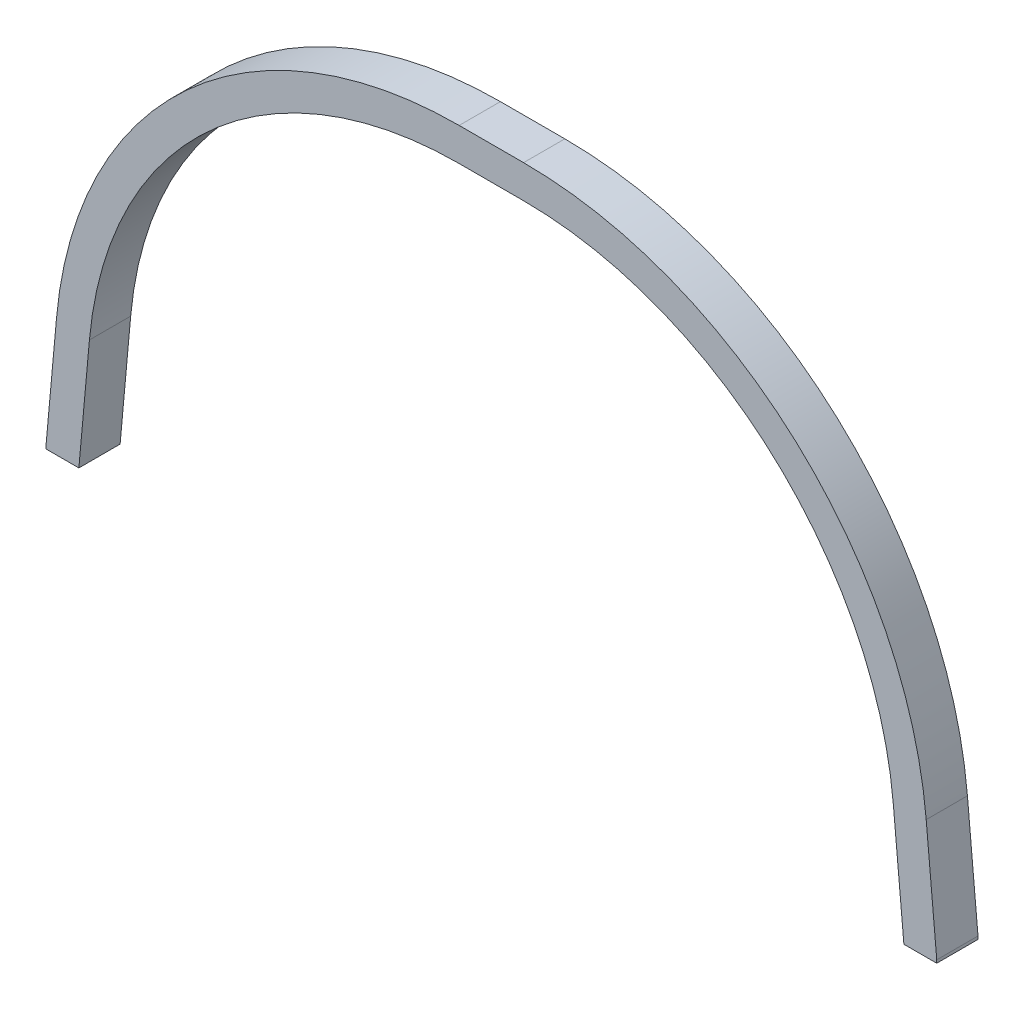
SolidWorks part; units mm, degrees
ref_plane "Front" through (0, 0, 0) normal (0, 0, 1) x (1, 0, 0)
ref_plane "Top" through (0, 0, 0) normal (0, 1, 0) x (1, 0, 0)
ref_plane "Right" through (0, 0, 0) normal (1, 0, 0) x (0, 0, -1)
sketch "草图1" plane through (0, 0, 0) normal (0, 0, 1) x (1, 0, 0)
  line L0 (0, 0) -> (0, 85)
  line L3 (125, 175) -> (355, 175)
  line L4 (355, 175) -> (355, 0)
  line L5 (355, 0) -> (317.5, 0)
  line L7 (312.5, 60) -> (222.5, 60)
  line L9 (217.5, 0) -> (137.5, 0)
  line L11 (132.5, 60) -> (42.5, 60)
  line L13 (37.5, 0) -> (0, 0)
  line L14 (37.5, 0) -> (37.5, 5)
  line L15 (37.5, 5) -> (42.5, 60)
  line L16 (137.5, 0) -> (137.5, 5)
  line L17 (137.5, 5) -> (132.5, 60)
  line L18 (217.5, 0) -> (217.5, 5)
  line L19 (217.5, 5) -> (222.5, 60)
  line L22 (312.5, 60) -> (317.5, 5)
  line L23 (317.5, 5) -> (317.5, 0)
  line L24 (125, 175) -> (110, 105)
  line L25 (110, 105) -> (0, 85)
  dimension "D1" = 85
  dimension "D2" = 37.5
  dimension "D3" = 0
  dimension "D4" = 100
  dimension "D5" = 90
  dimension "D6" = 80
  dimension "D7" = 100
  dimension "D8" = 90
  dimension "D9" = 37.5
  dimension "D10" = 70
  dimension "D11" = 20
  dimension "D12" = 5
  dimension "D13" = 15
  dimension "D15" = 60
  dimension "D16" = 60
  dimension "D18" = 230
  dimension "D19" = 5
  dimension "D20" = 5
  dimension "D21" = 5
extrude "凸台-拉伸1" add sketch "草图1" along normal blind 5
sketch "草图2" plane through (0, 0, 5) normal (0, 0, 1) x (1, 0, 0)
  line L0 (355, 175) -> (125, 175) construction
  circle A1 centre (200, 173) radius 1
  circle A2 centre (240, 173) radius 1
  circle A3 centre (280, 173) radius 1
  circle A4 centre (320, 173) radius 1
  circle A5 centre (160, 173) radius 1
  dimension "D2" = 2
  dimension "D3" = 40
  dimension "D4" = 2
  dimension "D7" = 0
  dimension "D8" = 40
  dimension "D9" = 40
  dimension "D10" = 2
  dimension "D11" = 40
  dimension "D12" = 0
sketch "草图3" plane through (0, 0, 5) normal (0, 0, 1) x (1, 0, 0)
  line L0 (355, 175) -> (125, 175) construction
  line L4 (167.5, 175) -> (167.5, 172)
  line L5 (355, 172) -> (327.5, 172)
  line L9 (207.5, 175) -> (207.5, 172)
  line L13 (247.5, 175) -> (247.5, 172)
  line L17 (287.5, 175) -> (287.5, 172)
  line L19 (312.5, 175) -> (312.5, 172)
  line L21 (327.5, 175) -> (327.5, 172)
  line L22 (355, 0) -> (355, 175) construction
  line L25 (192.5, 172) -> (167.5, 172)
  line L26 (232.5, 172) -> (207.5, 172)
  line L27 (272.5, 172) -> (247.5, 172)
  line L28 (312.5, 172) -> (287.5, 172)
  line L31 (167.5, 175) -> (192.5, 175)
  line L32 (207.5, 175) -> (232.5, 175)
  line L33 (247.5, 175) -> (272.5, 175)
  line L34 (287.5, 175) -> (312.5, 175)
  line L35 (327.5, 175) -> (355, 175)
  line L36 (355, 175) -> (355, 172)
  line L37 (152.5, 175) -> (152.5, 172)
  line L38 (192.5, 175) -> (192.5, 172)
  line L39 (232.5, 175) -> (232.5, 172)
  line L40 (272.5, 175) -> (272.5, 172)
  line L41 (152.5, 172) -> (124.3571, 172)
  line L42 (125, 175) -> (110, 105) construction
  line L44 (152.5, 175) -> (125, 175)
  line L45 (125, 175) -> (124.3571, 172)
  circle A4 centre (320, 173) radius 1 construction
  dimension "D15" = 7.5
  dimension "D1" = 15
  dimension "D2" = 3
  dimension "D4" = 3
  dimension "D5" = 15
  dimension "D7" = 3
  dimension "D8" = 15
  dimension "D10" = 3
  dimension "D11" = 15
  dimension "D13" = 15
  dimension "D14" = 3
extrude "切除-拉伸1" cut sketch "草图3" against normal through all
extrude "切除-拉伸2" cut sketch "草图2" against normal through all
sketch "草图4" plane through (0, 0, 5) normal (0, 0, 1) x (1, 0, 0)
  line L0 (355, 0) -> (355, 172) construction
  line L1 (327.5, 172) -> (355, 172) construction
  circle A0 centre (353, 162) radius 1
  circle A1 centre (353, 122) radius 1
  circle A2 centre (353, 82) radius 1
  circle A3 centre (353, 42) radius 1
  dimension "D1" = 2
  dimension "D2" = 2
  dimension "D3" = 2
  dimension "D4" = 40
  dimension "D5" = 40
  dimension "D6" = 2
  dimension "D7" = 40
  dimension "D8" = 10
extrude "切除-拉伸3" cut sketch "草图4" against normal through all
sketch "草图5" plane through (0, 0, 5) normal (0, 0, 1) x (1, 0, 0)
  line L0 (355, 0) -> (355, 172) construction
  line L1 (355, 152) -> (352, 152)
  line L2 (355, 152) -> (355, 132)
  line L3 (355, 132) -> (352, 132)
  line L4 (352, 152) -> (352, 132)
  line L6 (355, 112) -> (352, 112)
  line L7 (355, 112) -> (355, 92)
  line L8 (355, 92) -> (352, 92)
  line L9 (352, 112) -> (352, 92)
  line L10 (355, 72) -> (352, 72)
  line L11 (355, 72) -> (355, 52)
  line L12 (355, 52) -> (352, 52)
  line L13 (352, 72) -> (352, 52)
  line L14 (355, 32) -> (352, 32)
  line L15 (355, 32) -> (355, 12)
  line L16 (355, 12) -> (352, 12)
  line L17 (352, 32) -> (352, 12)
  circle A0 centre (353, 162) radius 1 construction
  circle A1 centre (353, 122) radius 1 construction
  circle A2 centre (353, 82) radius 1 construction
  circle A3 centre (353, 42) radius 1 construction
  dimension "D1" = 10
  dimension "D2" = 3
  dimension "D3" = 20
  dimension "D4" = 3
  dimension "D5" = 10
  dimension "D6" = 20
  dimension "D7" = 3
  dimension "D8" = 10
  dimension "D9" = 20
  dimension "D10" = 3
  dimension "D11" = 20
  dimension "D12" = 10
extrude "切除-拉伸4" cut sketch "草图5" against normal through all
sketch "草图6" plane through (0, 0, 5) normal (0, 0, 1) x (1, 0, 0)
  line L0 (137.5, 0) -> (217.5, 0) construction
  line L1 (162.5, 0) -> (109.536, 0)
  line L2 (162.5, 0) -> (162.5, 5)
  line L3 (162.5, 5) -> (109.536, 5)
  line L4 (109.536, 0) -> (109.536, 5)
  line L6 (192.5, 0) -> (242.7479, 0)
  line L7 (192.5, 0) -> (192.5, 5)
  line L8 (192.5, 5) -> (242.7479, 5)
  line L9 (242.7479, 0) -> (242.7479, 5)
  point P10 (177.5, 0)
  dimension "D1" = 5
  dimension "D2" = 5
  dimension "D3" = 15
  dimension "D4" = 15
extrude "切除-拉伸5" cut sketch "草图6" against normal through all
sketch "草图7" plane through (0, 0, 5) normal (0, 0, 1) x (1, 0, 0)
  line L0 (0, 0) -> (37.5, 0) construction
  line L1 (13.75, 0) -> (-10.7499, 0)
  line L2 (13.75, 0) -> (13.75, 5)
  line L3 (13.75, 5) -> (-10.7499, 5)
  line L4 (-10.7499, 0) -> (-10.7499, 5)
  line L5 (317.5, 0) -> (355, 0) construction
  line L6 (23.75, 0) -> (49.3843, 0)
  line L7 (23.75, 0) -> (23.75, 5)
  line L8 (23.75, 5) -> (49.3843, 5)
  line L9 (49.3843, 0) -> (49.3843, 5)
  line L10 (300.5943, 5) -> (331.25, 5)
  line L11 (300.5943, 5) -> (300.5943, 0)
  line L12 (300.5943, 0) -> (331.25, 0)
  line L13 (331.25, 5) -> (331.25, 0)
  line L14 (355, 0) -> (355, 12) construction
  line L15 (341.25, 5) -> (355, 5)
  line L16 (341.25, 5) -> (341.25, 0)
  line L17 (341.25, 0) -> (355, 0)
  line L18 (355, 5) -> (355, 0)
  point P10 (18.75, 0)
  point P17 (336.25, 0)
  dimension "D1" = 5
  dimension "D2" = 5
  dimension "D3" = 5
  dimension "D4" = 5
  dimension "D5" = 5
  dimension "D6" = 0
  dimension "D7" = 5
  dimension "D8" = 5
  dimension "D9" = 5
  dimension "D10" = 0
extrude "切除-拉伸6" cut sketch "草图7" against normal through all
sketch "草图11" plane through (0, 0, 5) normal (0, 0, 1) x (1, 0, 0)
  line L0 (114.2752, 110.6329) -> (111.3417, 111.2615)
  line L1 (124.3571, 172) -> (110, 105) construction
  line L2 (114.2752, 110.6329) -> (111.3417, 111.2615) construction
  line L3 (111.3417, 111.2615) -> (123.0754, 166.0184)
  line L4 (123.0754, 166.0184) -> (126.0088, 165.3898)
  line L5 (126.0088, 165.3898) -> (114.2752, 110.6329)
extrude "切除-拉伸10" cut sketch "草图11" against normal through all
sketch "草图12" plane through (0, 0, 5) normal (0, 0, 1) x (1, 0, 0)
  line L0 (0, 85) -> (0, 5) construction
  line L1 (0, 20) -> (10, 20)
  line L2 (0, 20) -> (0, 134.036)
  line L3 (0, 134.036) -> (10, 134.036)
  line L4 (10, 20) -> (10, 134.036)
  line L5 (13.75, 5) -> (0, 5) construction
  dimension "D1" = 10
  dimension "D2" = 15
extrude "切除-拉伸11" cut sketch "草图12" against normal through all
sketch "草图13" plane through (0, 0, 5) normal (0, 0, 1) x (1, 0, 0)
  line L0 (10, 20) -> (10, 86.8182) construction
  line L1 (10, 30) -> (5, 30)
  line L2 (10, 30) -> (10, 45)
  line L3 (10, 45) -> (5, 45)
  line L4 (5, 30) -> (5, 45)
  line L5 (0, 20) -> (10, 20) construction
  line L7 (10, 60) -> (5, 60)
  line L8 (10, 60) -> (10, 75)
  line L9 (10, 75) -> (5, 75)
  line L10 (5, 60) -> (5, 75)
  dimension "D1" = 5
  dimension "D2" = 15
  dimension "D3" = 10
  dimension "D4" = 15
  dimension "D5" = 15
extrude "凸台-拉伸2" add sketch "草图13" against normal blind 3
sketch "草图15" plane through (0, 0, 5) normal (0, 0, 1) x (1, 0, 0)
  line L2 (35.4912, 86.371) -> (34.5967, 91.2903)
  line L3 (110, 105) -> (10, 86.8182) construction
  line L5 (54.2741, 94.868) -> (55.1686, 89.9487)
  line L6 (55.1686, 89.9487) -> (69.9266, 92.632)
  line L7 (69.9266, 92.632) -> (69.0322, 97.5513)
  line L8 (69.0322, 97.5513) -> (54.2741, 94.868)
  line L9 (88.7096, 101.129) -> (89.604, 96.2097)
  line L10 (89.604, 96.2097) -> (104.3621, 98.8929)
  line L11 (104.3621, 98.8929) -> (103.4676, 103.8123)
  line L12 (103.4676, 103.8123) -> (88.7096, 101.129)
  line L13 (35.4912, 86.371) -> (20.7331, 83.6877)
  line L14 (20.7331, 83.6877) -> (19.8387, 88.607)
  line L15 (19.8387, 88.607) -> (34.5967, 91.2903)
  dimension "D1" = 10
  dimension "D2" = 5
  dimension "D3" = 5
  dimension "D4" = 15
  dimension "D5" = 20
  dimension "D6" = 15
  dimension "D7" = 5
  dimension "D8" = 20
  dimension "D9" = 15
extrude "切除-拉伸12" cut sketch "草图15" against normal through all
fillet "圆角1" radius 45 4 edges at (312.5, 60, 2.5) (222.5, 60, 2.5) (132.5, 60, 2.5) (42.5, 60, 2.5)
sketch "草图16" plane through (0, 0, 5) normal (0, 0, 1) x (1, 0, 0)
  line L1 (37.5, 5) -> (23.75, 5) construction
  line L2 (33.5164, 5) -> (33.5164, 5.3621)
  line L4 (162.5, 5) -> (137.5, 5) construction
  line L5 (141.4836, 5) -> (141.4836, 5.3621)
  line L6 (140.2041, 19.4363) -> (141.4836, 5.3621)
  line L7 (83.5947, 64) -> (91.4053, 64)
  line L8 (33.5164, 5.3621) -> (34.7959, 19.4363)
  line L9 (140.2041, 19.4363) -> (141.4836, 5.3621)
  line L10 (0, 5) -> (0, 20)
  line L11 (0, 20) -> (5, 75)
  line L12 (5, 75) -> (10, 86.8182)
  line L13 (10, 86.8182) -> (88.7096, 101.129)
  line L14 (83.5947, 64) -> (91.4053, 64)
  line L15 (33.5164, 5.3621) -> (34.7959, 19.4363)
  line L16 (88.7096, 101.129) -> (124.3571, 172)
  line L17 (124.3571, 172) -> (152.5, 175)
  line L18 (33.5164, 5) -> (23.75, 0)
  line L19 (23.75, 0) -> (13.75, 0)
  line L20 (13.75, 0) -> (0, 5)
  line L27 (152.5, 175) -> (327.5, 175)
  line L28 (327.5, 175) -> (355, 172)
  line L29 (355, 172) -> (355, 5)
  line L30 (355, 5) -> (341.25, 0)
  line L31 (341.25, 0) -> (331.25, 0)
  line L32 (331.25, 0) -> (317.5, 5)
  line L33 (317.5, 5) -> (217.5, 5)
  line L34 (217.5, 5) -> (192.5, 0)
  line L35 (192.5, 0) -> (162.5, 0)
  line L36 (162.5, 0) -> (141.4836, 5)
  arc A5 (140.2041, 19.4363) -> (91.4053, 64) centre (91.4053, 15) ccw
  arc A6 (83.5947, 64) -> (34.7959, 19.4363) centre (83.5947, 15) ccw
  arc A7 (140.2041, 19.4363) -> (91.4053, 64) centre (91.4053, 15) ccw
  arc A8 (83.5947, 64) -> (34.7959, 19.4363) centre (83.5947, 15) ccw
  dimension "D1" = 4
extrude "切除-拉伸13" cut sketch "草图16" against normal through all contours L12 L13 L16 L17 L27 L28 L29 L30 L31 L32 L33 L34 L35 L36 L5 L9 A7 L14 A8 L15 L2 L18 L19 L20 L10 L11
